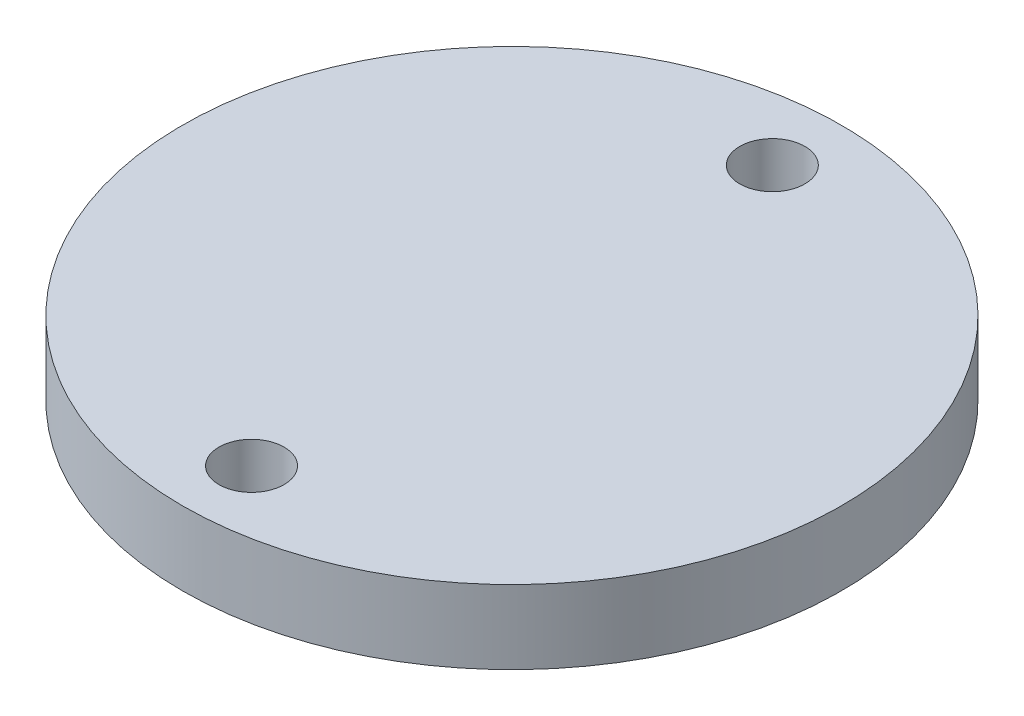
SolidWorks part; units mm, degrees
ref_plane "Front Plane" through (0, 0, 0) normal (0, 0, 1) x (1, 0, 0)
ref_plane "Top Plane" through (0, 0, 0) normal (0, 1, 0) x (1, 0, 0)
ref_plane "Right Plane" through (0, 0, 0) normal (1, 0, 0) x (0, 0, -1)
sketch "Sketch1" plane through (0, 0, 0) normal (0, 1, 0) x (1, 0, 0)
  circle A0 centre (0, 0) radius 10.287
  dimension "D1" = 20.574
extrude "Boss-Extrude1" add sketch "Sketch1" along normal blind 2.3
sketch "Sketch2" plane through (0, 0, 0) normal (0, -1, 0) x (-1, 0, 0)
  circle A0 centre (0, 0) radius 4.4
  dimension "D1" = 8.8
extrude "Boss-Extrude2" add sketch "Sketch2" along normal blind 3.3
sketch "Sketch4" plane through (0, 0, 0) normal (0, 1, 0) x (1, 0, 0)
  circle A0 centre (0, 8.128) radius 1.016
  circle A1 centre (0, -8.128) radius 1.016
  point P4 (0, 0)
  point P6 (0, 0)
  dimension "D1" = 2.032
  dimension "D2" = 2.032
  dimension "D3" = 8.128
  dimension "D4" = 8.128
  dimension "D5" = 16.256
extrude "Cut-Extrude1" cut sketch "Sketch4" along normal up to surface (2.3 mm away) up to face at (0, 2.3, 10.287)
